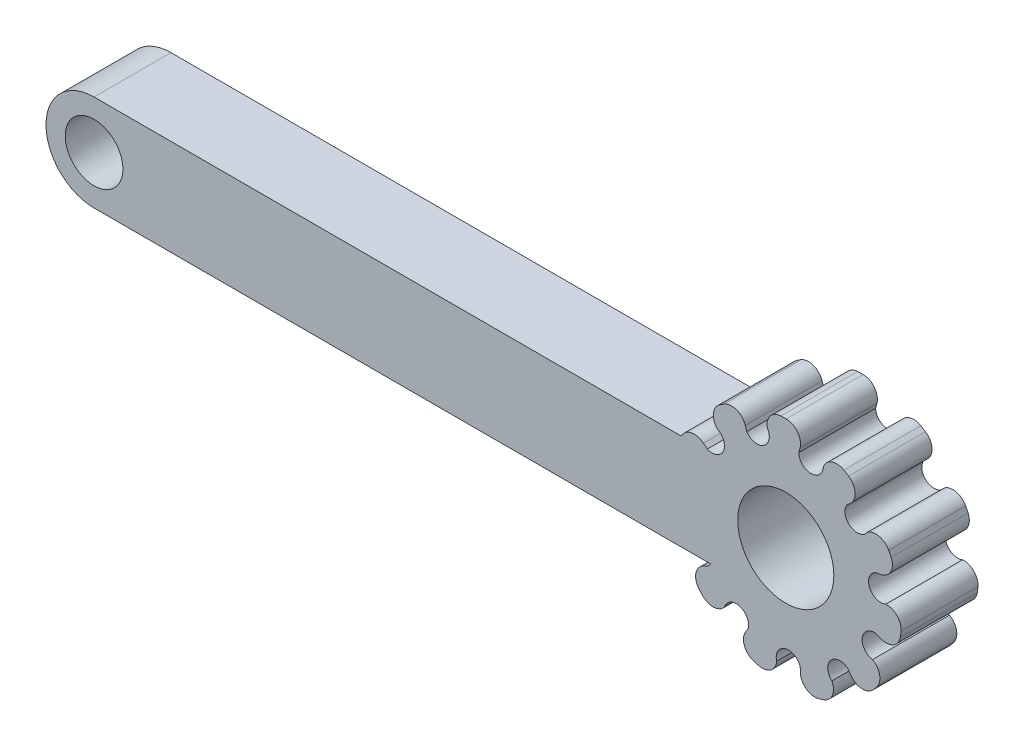
SolidWorks part; units mm, degrees
ref_plane "Front Plane" through (0, 0, 0) normal (0, 0, 1) x (1, 0, 0)
ref_plane "Top Plane" through (0, 0, 0) normal (0, 1, 0) x (1, 0, 0)
ref_plane "Right Plane" through (0, 0, 0) normal (1, 0, 0) x (0, 0, -1)
sketch "Sketch1" plane through (0, 0, 0) normal (0, 0, 1) x (1, 0, 0)
  line L0 (-18, 0) -> (-16.5, 0) construction
  line L1 (-18, 0) -> (-18, 2.5) construction
  line L2 (-18, 2.5) -> (12.5456, 2.5)
  line L3 (-18, -2.5) -> (12.5456, -2.5)
  arc A0 (-18, 2.5) -> (-18, -2.5) centre (-18, 0) ccw
  circle A1 centre (-18, 0) radius 1.5
  arc A2 (12.5456, -2.5) -> (12.5456, 2.5) centre (18, 0) ccw
  point P4 (0, 0)
  dimension "D2" = 3
  dimension "D3" = 5
  dimension "D4" = 12
  dimension "D1" = 36
extrude "Boss-Extrude1" add sketch "Sketch1" along normal blind 4
sketch "Sketch2" plane through (0, 0, 4) normal (0, 0, 1) x (1, 0, 0)
  line L0 (18, 6) -> (18, -6) construction
  line L1 (18, 0) -> (21, 5.1962) construction
  line L2 (18, 0) -> (19.2915, 4.82) construction
  line L3 (18.72, 5.06) -> (18.653, 4.81)
  line L4 (18.653, 4.81) -> (20.2127, 4.81) construction
  arc A0 (12.5456, -2.5) -> (12.5456, 2.5) centre (18, 0) ccw construction
  arc A1 (18, 6) -> (18.72, 5.06) centre (17.9945, 5.25) cw
  arc A2 (18.653, 4.81) -> (19.93, 4.81) centre (19.2915, 4.82) ccw
  arc A3 (21, 5.1962) -> (19.9302, 4.8143) centre (20.6298, 4.5439) ccw
  arc A4 (19.93, 4.81) -> (19.9302, 4.8143) centre (19.9916, 4.809) cw
  arc A5 (18, 6) -> (21, 5.1962) centre (18, 0) cw
  dimension "D6" = 0.75
  dimension "D1" = 30
  dimension "D2" = 4.82
  dimension "D3" = 15
  dimension "D4" = 0.94
  dimension "D5" = 0.72
  dimension "D7" = 15
  dimension "D8" = 0.25
extrude "Cut-Extrude1" cut sketch "Sketch2" against normal blind 4
pattern_circular "CirPattern2" count 11 over 360 about axis through (18, 0, 0) along (0, 0, 1) of "Cut-Extrude1"
sketch "Sketch3" plane through (0, 0, 4) normal (0, 0, 1) x (1, 0, 0)
  line L0 (12.5456, 2.5) -> (-18, 2.5) construction
  line L1 (9.0255, 2.5) -> (15.1191, 2.5)
  line L2 (9.0255, 2.5) -> (9.0255, -2.4962)
  line L3 (9.0255, -2.4962) -> (15.1191, -2.4962)
  line L4 (15.1191, 2.5) -> (15.1191, -2.4962)
extrude "Boss-Extrude2" add sketch "Sketch3" against normal blind 4
sketch "Sketch4" plane through (0, 0, 4) normal (0, 0, 1) x (1, 0, 0)
  line L0 (17.8572, 5.9983) -> (18.0954, -5.6268) construction
  arc A0 (18, 6) -> (17.7145, 5.9932) centre (18, 0) ccw construction
  arc A1 (18.7286, -4.7991) -> (17.5033, -5.1589) centre (18.1188, -4.9886) ccw construction
  circle A2 centre (17.9763, 0.1858) radius 2.5
  dimension "D1" = 5
extrude "Cut-Extrude2" cut sketch "Sketch4" against normal blind 4
